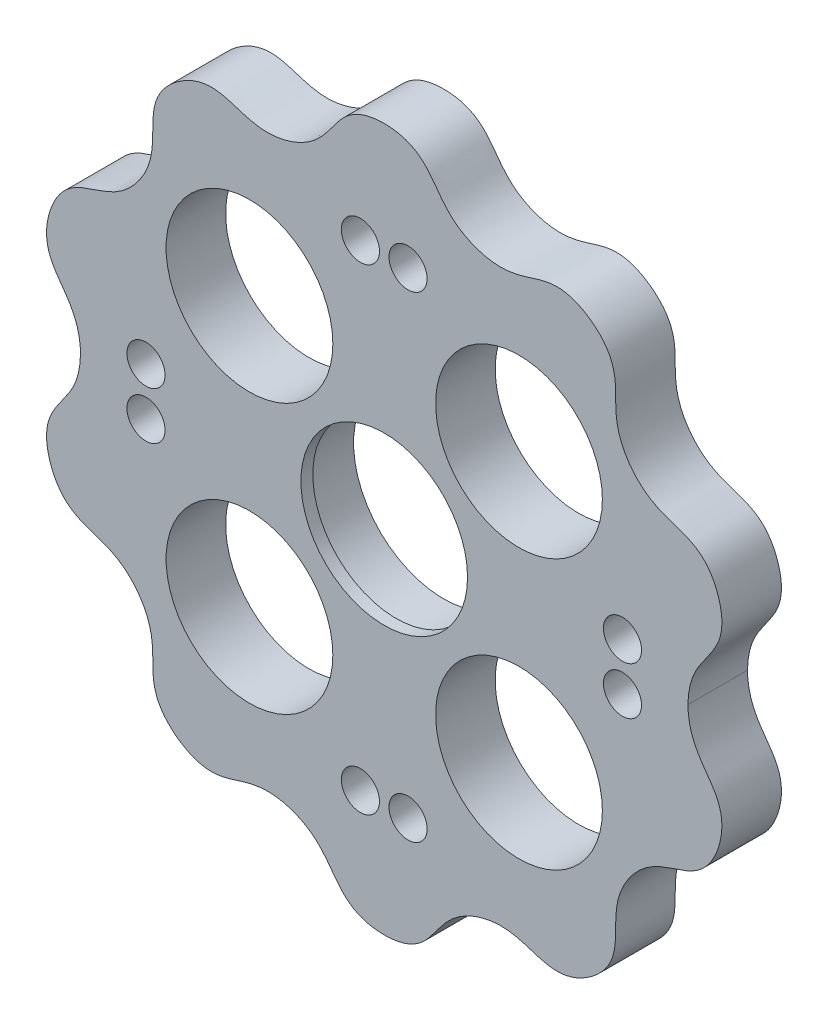
SolidWorks part; units mm, degrees
ref_plane "Front Plane" through (0, 0, 0) normal (0, 0, 1) x (1, 0, 0)
ref_plane "Top Plane" through (0, 0, 0) normal (0, 1, 0) x (1, 0, 0)
ref_plane "Right Plane" through (0, 0, 0) normal (1, 0, 0) x (0, 0, -1)
ref_plane "Plane1" through (0, 0, 4) normal (0, 0, 1) x (1, 0, 0)
sketch "Sketch3" plane through (0, 0, 4) normal (0, 0, 1) x (1, 0, 0)
  circle A0 centre (2, 0) radius 7.5
  spline S0 degree 5 poles (-23.5, 0) (-23.5, -0.6619) (-23.5985, -1.4561) (-23.8874, -2.4734) (-24.5265, -3.4803) (-25.3239, -4.5428) (-25.7599, -5.1922) (-26.203, -6.107) (-26.3992, -6.9747) (-26.3685, -8.1757) (-26.0322, -9.4106) (-25.4671, -10.5179) (-24.8895, -11.2256) (-23.9802, -11.9083) (-23.1576, -12.2723) (-21.7572, -12.687) (-20.1242, -13.2676) (-18.7699, -14.5833) (-17.7259, -16.1905) (-17.3933, -18.0022) (-17.4393, -19.3418) (-17.4288, -20.3924) (-17.2271, -21.518) (-16.8759, -22.3353) (-16.145, -23.2889) (-15.1471, -24.0902) (-14.0391, -24.6539) (-13.1558, -24.8869) (-12.0189, -24.9048) (-11.1394, -24.7158) (-9.7628, -24.2281) (-8.1004, -23.738) (-6.2314, -24.0063) (-4.442, -24.693) (-3.1081, -25.9632) (-2.3579, -27.074) (-1.7319, -27.9177) (-0.9071, -28.7098) (-0.1425, -29.1646) (1.0093, -29.5065) (2.2876, -29.5682) (3.5153, -29.373) (4.3668, -29.0423) (5.2971, -28.3885) (5.8976, -27.7187) (6.7246, -26.515) (7.7814, -25.1413) (9.4513, -24.2598) (11.3025, -23.7636) (13.1282, -24.0071) (14.3881, -24.4648) (15.3905, -24.7795) (16.5233, -24.9355) (17.4092, -24.854) (18.5419, -24.4536) (19.6124, -23.7522) (20.4909, -22.8726) (20.9855, -22.1045) (21.3538, -21.0288) (21.4458, -20.1339) (21.4074, -18.674) (21.455, -16.9415) (22.2878, -15.2469) (23.4937, -13.7573) (25.1139, -12.8812) (26.4022, -12.5109) (27.3981, -12.1763) (28.4063, -11.6367) (29.0751, -11.05) (29.7562, -10.0602) (30.2099, -8.8636) (30.4037, -7.6356) (30.3523, -6.7236) (30.018, -5.6368) (29.5664, -4.8587) (28.6772, -3.7002) (27.9235, -2.6005) (27.5985, -1.4561) (27.5, -0.6619) (27.5, 0) knots 0.5 0.5 0.5 0.5 0.5 0.5 0.516667 0.52 0.526667 0.53 0.533333 0.536667 0.546667 0.55 0.56 0.563333 0.566667 0.57 0.58 0.583333 0.6 0.61 0.616667 0.626667 0.63 0.633333 0.636667 0.646667 0.65 0.66 0.663333 0.666667 0.67 0.68 0.683333 0.7 0.71 0.716667 0.726667 0.73 0.733333 0.736667 0.746667 0.75 0.76 0.763333 0.766667 0.77 0.78 0.783333 0.8 0.81 0.816667 0.826667 0.83 0.833333 0.836667 0.846667 0.85 0.86 0.863333 0.866667 0.87 0.88 0.883333 0.9 0.91 0.916667 0.926667 0.93 0.933333 0.936667 0.946667 0.95 0.96 0.963333 0.966667 0.97 0.98 0.983333 1 1 1 1 1 1 weights 1 1 1 1 1 1 1 1 1 1 1 1 1 1 1 1 1 1 1 1 1 1 1 1 1 1 1 1 1 1 1 1 1 1 1 1 1 1 1 1 1 1 1 1 1 1 1 1 1 1 1 1 1 1 1 1 1 1 1 1 1 1 1 1 1 1 1 1 1 1 1 1 1 1 1 1 1 1 1 1
  spline S1 degree 5 poles (27.5, 0) (27.5, 0.6619) (27.5985, 1.4561) (27.8874, 2.4734) (28.5265, 3.4803) (29.3239, 4.5428) (29.7599, 5.1922) (30.203, 6.107) (30.3992, 6.9747) (30.3685, 8.1757) (30.0322, 9.4106) (29.4671, 10.5179) (28.8895, 11.2256) (27.9802, 11.9083) (27.1576, 12.2723) (25.7572, 12.687) (24.1242, 13.2676) (22.7699, 14.5833) (21.7259, 16.1905) (21.3933, 18.0022) (21.4393, 19.3418) (21.4288, 20.3924) (21.2271, 21.518) (20.8759, 22.3353) (20.145, 23.2889) (19.1471, 24.0902) (18.0391, 24.6539) (17.1558, 24.8869) (16.0189, 24.9048) (15.1394, 24.7158) (13.7628, 24.2281) (12.1004, 23.738) (10.2314, 24.0063) (8.442, 24.693) (7.1081, 25.9632) (6.3579, 27.074) (5.7319, 27.9177) (4.9071, 28.7098) (4.1425, 29.1646) (2.9907, 29.5065) (1.7124, 29.5682) (0.4847, 29.373) (-0.3668, 29.0423) (-1.2971, 28.3885) (-1.8976, 27.7187) (-2.7246, 26.515) (-3.7814, 25.1413) (-5.4513, 24.2598) (-7.3025, 23.7636) (-9.1282, 24.0071) (-10.3881, 24.4648) (-11.3905, 24.7795) (-12.5233, 24.9355) (-13.4092, 24.854) (-14.5419, 24.4536) (-15.6124, 23.7522) (-16.4909, 22.8726) (-16.9855, 22.1045) (-17.3538, 21.0288) (-17.4458, 20.1339) (-17.4074, 18.674) (-17.455, 16.9415) (-18.2878, 15.2469) (-19.4937, 13.7573) (-21.1139, 12.8812) (-22.4022, 12.5109) (-23.3981, 12.1763) (-24.4063, 11.6367) (-25.0751, 11.05) (-25.7562, 10.0602) (-26.2099, 8.8636) (-26.4037, 7.6356) (-26.3523, 6.7236) (-26.018, 5.6368) (-25.5664, 4.8587) (-24.6772, 3.7002) (-23.9235, 2.6005) (-23.5985, 1.4561) (-23.5, 0.6619) (-23.5, 0) knots 0 0 0 0 0 0 0.016667 0.02 0.026667 0.03 0.033333 0.036667 0.046667 0.05 0.06 0.063333 0.066667 0.07 0.08 0.083333 0.1 0.11 0.116667 0.126667 0.13 0.133333 0.136667 0.146667 0.15 0.16 0.163333 0.166667 0.17 0.18 0.183333 0.2 0.21 0.216667 0.226667 0.23 0.233333 0.236667 0.246667 0.25 0.26 0.263333 0.266667 0.27 0.28 0.283333 0.3 0.31 0.316667 0.326667 0.33 0.333333 0.336667 0.346667 0.35 0.36 0.363333 0.366667 0.37 0.38 0.383333 0.4 0.41 0.416667 0.426667 0.43 0.433333 0.436667 0.446667 0.45 0.46 0.463333 0.466667 0.47 0.48 0.483333 0.5 0.5 0.5 0.5 0.5 0.5 weights 1 1 1 1 1 1 1 1 1 1 1 1 1 1 1 1 1 1 1 1 1 1 1 1 1 1 1 1 1 1 1 1 1 1 1 1 1 1 1 1 1 1 1 1 1 1 1 1 1 1 1 1 1 1 1 1 1 1 1 1 1 1 1 1 1 1 1 1 1 1 1 1 1 1 1 1 1 1 1 1
extrude "CYC Disk" add sketch "Sketch3" along normal blind 5
sketch "Sketch6" plane through (0, 0, 9) normal (0, 0, 1) x (1, 0, 0)
  line L0 (0, 0) -> (2, 0) construction
  circle A1 centre (2, 0) radius 7.575
  dimension "D2" = 15.15
  dimension "D1" = 2
extrude "Cam Bearing" cut sketch "Sketch6" against normal through all
sketch "Sketch7" plane through (0, 0, 9) normal (0, 0, 1) x (1, 0, 0)
  line L0 (2, 0) -> (18, 0) construction
  line L1 (2, 0) -> (13.3137, 11.3137) construction
  circle A0 centre (2, 0) radius 16 construction
  circle A1 centre (13.3137, 11.3137) radius 7
  circle A2 centre (13.3137, -11.3137) radius 7
  circle A3 centre (-9.3137, -11.3137) radius 7
  circle A4 centre (-9.3137, 11.3137) radius 7
  point P15 (2, 0)
  dimension "D1" = 32
  dimension "D2" = 45
  dimension "D3" = 14
  dimension "D4" = 4
extrude "Output Holes" cut sketch "Sketch7" against normal through all
sketch "Sketch8" plane through (0, 0, 9) normal (0, 0, 1) x (1, 0, 0)
  circle A0 centre (2, 0) radius 6.9953
  circle A1 centre (2, 0) radius 7.575
extrude "Cam Bearing Retainer" add sketch "Sketch8" against normal blind 1
sketch "Sketch9" plane through (0, 0, 9) normal (0, 0, 1) x (1, 0, 0)
  line L0 (2, 0) -> (2, 20) construction
  line L2 (4, 20) -> (2, 20)
  line L3 (2, 20) -> (0, 20)
  circle A2 centre (0, 20) radius 1.6
  circle A3 centre (4, 20) radius 1.6
  circle A4 centre (22, -2) radius 1.6
  circle A5 centre (22, 2) radius 1.6
  circle A6 centre (0, -20) radius 1.6
  circle A7 centre (4, -20) radius 1.6
  circle A8 centre (-18, 2) radius 1.6
  circle A9 centre (-18, -2) radius 1.6
  point P8 (2, 0)
  point P23 (2, 0)
  dimension "D3" = 2
  dimension "D4" = 3.2
  dimension "D5" = 3.2
  dimension "D6" = 4
  dimension "D1" = 2
  dimension "D2" = 20
extrude "Positioning Holes" cut sketch "Sketch9" against normal through all
equation "\"CamBearingOut\"=15.15"
equation "\"D2@Sketch6\"=\"CamBearingOut\""
equation "\"RingPinShaft\"= 5"
equation "\"CenterBearingOut\"=32"
equation "\"RingPostIn\"=5"
